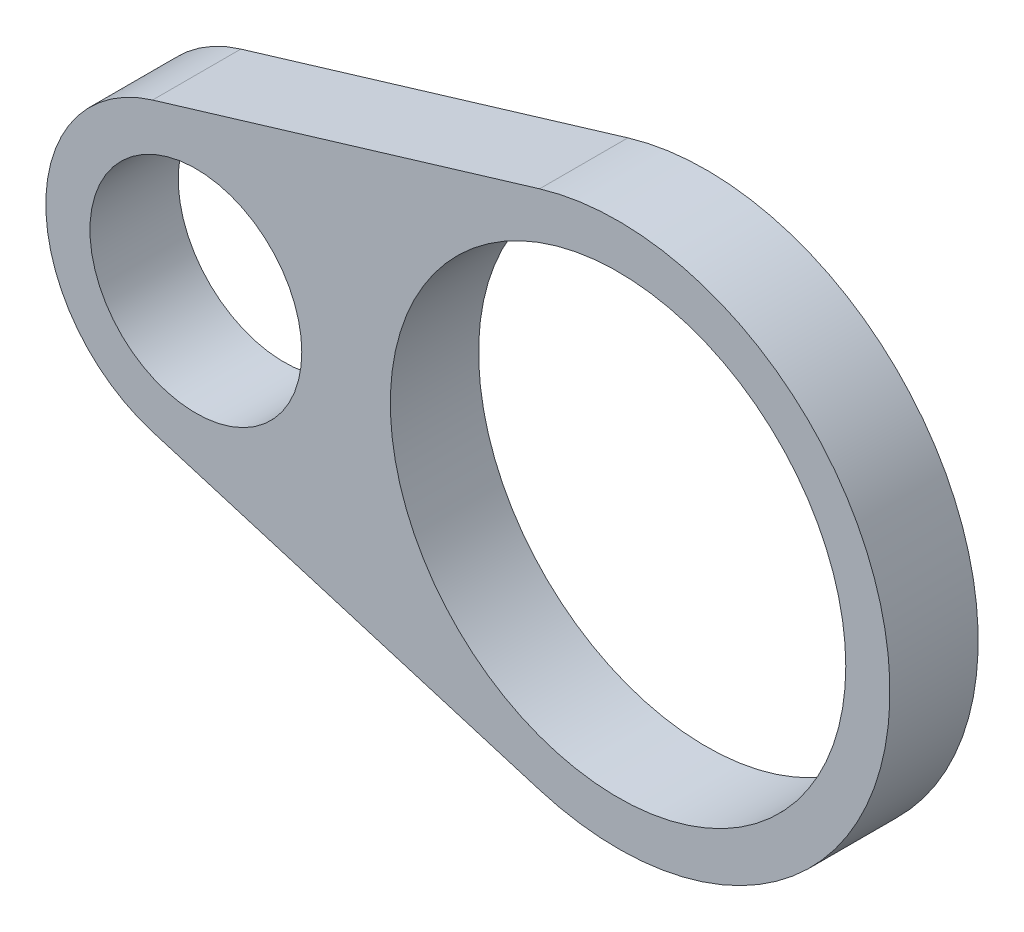
SolidWorks part; units mm, degrees
ref_plane "Plano frontal" through (0, 0, 0) normal (0, 0, 1) x (1, 0, 0)
ref_plane "Plano superior" through (0, 0, 0) normal (0, 1, 0) x (1, 0, 0)
ref_plane "Plano direito" through (0, 0, 0) normal (1, 0, 0) x (0, 0, -1)
sketch "Esboço2" plane through (0, 0, 0) normal (0, 0, 1) x (1, 0, 0)
  line L0 (-23.915, 0) -> (23.915, 0) construction
  line L1 (-28.8199, 16.277) -> (15.0285, 29.4902)
  line L2 (-28.8199, -16.277) -> (15.0285, -29.4902)
  circle A0 centre (23.915, 0) radius 25.8
  circle A1 centre (-23.915, 0) radius 12
  arc A2 (-28.8199, 16.277) -> (-28.8199, -16.277) centre (-23.915, 0) ccw
  arc A3 (15.0285, -29.4902) -> (15.0285, 29.4902) centre (23.915, 0) ccw
  circle A4 centre (23.915, 0) radius 30.8 construction
  circle A5 centre (-23.915, 0) radius 17 construction
  point P4 (0, 0)
  dimension "D1" = 5
  dimension "D2" = 24
  dimension "D3" = 51.6
  dimension "D4" = 47.83
extrude "Ressalto-extrusão1" add sketch "Esboço2" along normal blind 10
